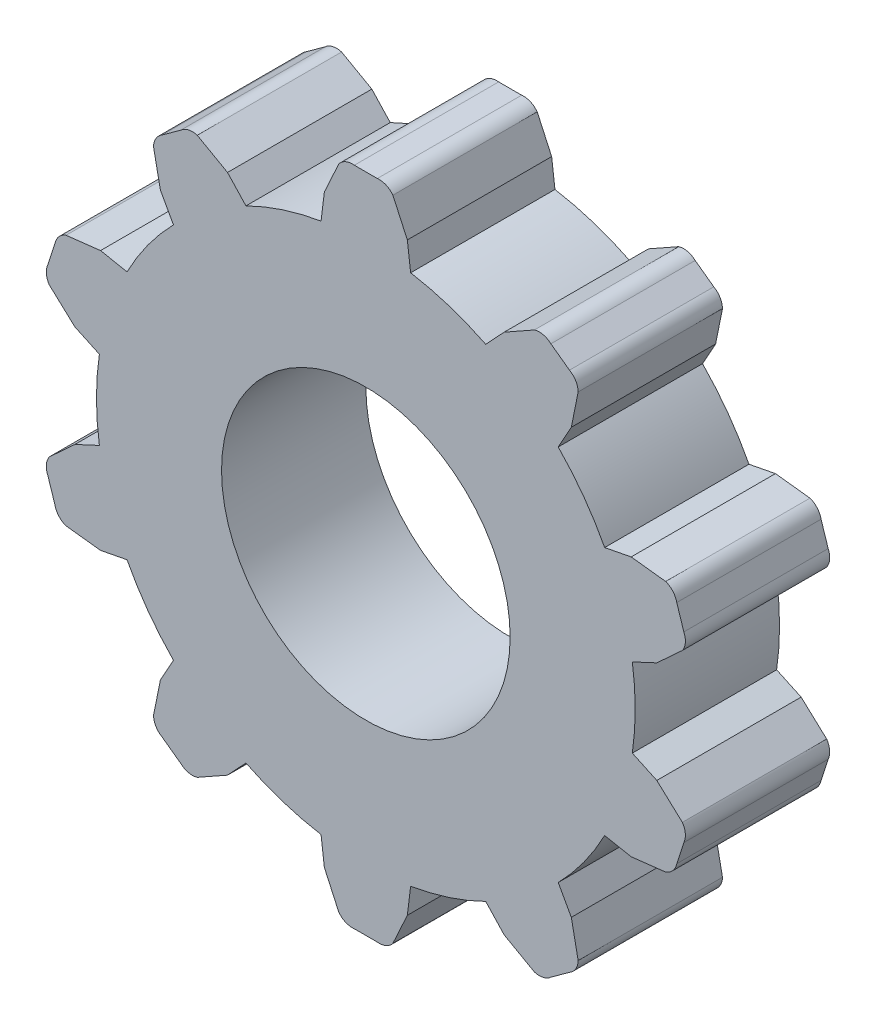
SolidWorks part; units mm, degrees
ref_plane "Płaszczyzna przednia" through (0, 0, 0) normal (0, 0, 1) x (1, 0, 0)
ref_plane "Płaszczyzna górna" through (0, 0, 0) normal (0, 1, 0) x (1, 0, 0)
ref_plane "Płaszczyzna prawa" through (0, 0, 0) normal (1, 0, 0) x (0, 0, -1)
sketch "Szkic1" plane through (0, 0, 0) normal (0, 0, 1) x (1, 0, 0)
  line L0 (0, 0) -> (-77.7801, 0) construction
  line L2 (-48.2003, 55.2206) -> (-47.5168, 60.795)
  line L3 (-47.5168, 60.795) -> (-44.5104, 67.3544)
  line L4 (-41.2805, 68.7348) -> (-36.4997, 68.7348)
  line L5 (-38.8901, 0) -> (-38.8901, 42.4347) construction
  line L6 (-29.5799, 55.2206) -> (-30.2633, 60.795)
  line L7 (-30.2633, 60.795) -> (-33.2697, 67.3544)
  line L8 (-10.1348, 54.2549) -> (-3.8471, 57.7944)
  line L9 (-13.9643, 50.1468) -> (-10.1348, 54.2549)
  line L10 (-0.4227, 57.0126) -> (3.4451, 54.2026)
  line L11 (3.8235, 44.1136) -> (5.2468, 51.1873)
  line L12 (1.0999, 39.202) -> (3.8235, 44.1136)
  line L13 (16.2636, 26.9912) -> (23.431, 26.1589)
  line L14 (10.7509, 25.9186) -> (16.2636, 26.9912)
  line L15 (25.7419, 23.5136) -> (27.2193, 18.9668)
  line L16 (21.5953, 10.5822) -> (26.9046, 15.4684)
  line L17 (16.5049, 8.2096) -> (21.5953, 10.5822)
  line L18 (21.5953, -10.5822) -> (26.9046, -15.4684)
  line L19 (16.5049, -8.2096) -> (21.5953, -10.5822)
  line L20 (27.2193, -18.9668) -> (25.7419, -23.5136)
  line L21 (16.2636, -26.9912) -> (23.431, -26.1589)
  line L22 (10.7509, -25.9186) -> (16.2636, -26.9912)
  line L23 (3.8235, -44.1136) -> (5.2468, -51.1873)
  line L24 (1.0999, -39.202) -> (3.8235, -44.1136)
  line L25 (3.4451, -54.2026) -> (-0.4227, -57.0126)
  line L26 (-10.1348, -54.2549) -> (-3.8471, -57.7944)
  line L27 (-13.9643, -50.1468) -> (-10.1348, -54.2549)
  line L28 (-30.2633, -60.795) -> (-33.2697, -67.3544)
  line L29 (-29.5799, -55.2206) -> (-30.2633, -60.795)
  line L30 (-36.4997, -68.7348) -> (-41.2805, -68.7348)
  line L31 (-47.5168, -60.795) -> (-44.5104, -67.3544)
  line L32 (-48.2003, -55.2206) -> (-47.5168, -60.795)
  line L33 (-67.6453, -54.2549) -> (-73.9331, -57.7944)
  line L34 (-63.8158, -50.1468) -> (-67.6453, -54.2549)
  line L35 (-77.3575, -57.0126) -> (-81.2252, -54.2026)
  line L36 (-81.6037, -44.1136) -> (-83.027, -51.1873)
  line L37 (-78.8801, -39.202) -> (-81.6037, -44.1136)
  line L38 (-94.0438, -26.9912) -> (-101.2112, -26.1589)
  line L39 (-88.531, -25.9186) -> (-94.0438, -26.9912)
  line L40 (-103.522, -23.5136) -> (-104.9994, -18.9668)
  line L41 (-99.3754, -10.5822) -> (-104.6847, -15.4684)
  line L42 (-94.285, -8.2096) -> (-99.3754, -10.5822)
  line L43 (-99.3754, 10.5822) -> (-104.6847, 15.4684)
  line L44 (-94.285, 8.2096) -> (-99.3754, 10.5822)
  line L45 (-104.9994, 18.9668) -> (-103.522, 23.5136)
  line L46 (-94.0438, 26.9912) -> (-101.2112, 26.1589)
  line L47 (-88.531, 25.9186) -> (-94.0438, 26.9912)
  line L48 (-81.6037, 44.1136) -> (-83.027, 51.1873)
  line L49 (-78.8801, 39.202) -> (-81.6037, 44.1136)
  line L50 (-81.2252, 54.2026) -> (-77.3575, 57.0126)
  line L51 (-67.6453, 54.2549) -> (-73.9331, 57.7944)
  line L52 (-63.8158, 50.1468) -> (-67.6453, 54.2549)
  circle A0 centre (-38.8901, 0) radius 30
  arc A1 (-78.8801, 39.202) -> (-88.531, 25.9186) centre (-38.8901, 0) ccw
  arc A2 (-44.5104, 67.3544) -> (-41.2805, 68.7348) centre (-41.6821, 65.2055) cw
  arc A3 (-33.2697, 67.3544) -> (-36.4997, 68.7348) centre (-36.098, 65.2055) ccw
  arc A4 (-3.8471, 57.7944) -> (-0.4227, 57.0126) centre (-2.8221, 54.3935) cw
  arc A5 (5.2468, 51.1873) -> (3.4451, 54.2026) centre (1.6956, 51.1112) ccw
  arc A6 (23.431, 26.1589) -> (25.7419, 23.5136) centre (22.2612, 22.805) cw
  arc A7 (26.9046, 15.4684) -> (27.2193, 18.9668) centre (23.9868, 17.4942) ccw
  arc A8 (26.9046, -15.4684) -> (27.2193, -18.9668) centre (23.9868, -17.4942) cw
  arc A9 (23.431, -26.1589) -> (25.7419, -23.5136) centre (22.2612, -22.805) ccw
  arc A10 (5.2468, -51.1873) -> (3.4451, -54.2026) centre (1.6956, -51.1112) cw
  arc A11 (-3.8471, -57.7944) -> (-0.4227, -57.0126) centre (-2.8221, -54.3935) ccw
  arc A12 (-33.2697, -67.3544) -> (-36.4997, -68.7348) centre (-36.098, -65.2055) cw
  arc A13 (-44.5104, -67.3544) -> (-41.2805, -68.7348) centre (-41.6821, -65.2055) ccw
  arc A14 (-73.9331, -57.7944) -> (-77.3575, -57.0126) centre (-74.9581, -54.3935) cw
  arc A15 (-83.027, -51.1873) -> (-81.2252, -54.2026) centre (-79.4757, -51.1112) ccw
  arc A16 (-101.2112, -26.1589) -> (-103.522, -23.5136) centre (-100.0414, -22.805) cw
  arc A17 (-104.6847, -15.4684) -> (-104.9994, -18.9668) centre (-101.7669, -17.4942) ccw
  arc A18 (-104.6847, 15.4684) -> (-104.9994, 18.9668) centre (-101.7669, 17.4942) cw
  arc A19 (-101.2112, 26.1589) -> (-103.522, 23.5136) centre (-100.0414, 22.805) ccw
  arc A20 (-83.027, 51.1873) -> (-81.2252, 54.2026) centre (-79.4757, 51.1112) cw
  arc A21 (-73.9331, 57.7944) -> (-77.3575, 57.0126) centre (-74.9581, 54.3935) ccw
  arc A22 (-94.285, 8.2096) -> (-94.285, -8.2096) centre (-38.8901, 0) ccw
  arc A23 (-88.531, -25.9186) -> (-78.8801, -39.202) centre (-38.8901, 0) ccw
  arc A24 (-63.8158, -50.1468) -> (-48.2003, -55.2206) centre (-38.8901, 0) ccw
  arc A25 (-29.5799, -55.2206) -> (-13.9643, -50.1468) centre (-38.8901, 0) ccw
  arc A26 (1.0999, -39.202) -> (10.7509, -25.9186) centre (-38.8901, 0) ccw
  arc A27 (16.5049, -8.2096) -> (16.5049, 8.2096) centre (-38.8901, 0) ccw
  arc A28 (10.7509, 25.9186) -> (1.0999, 39.202) centre (-38.8901, 0) ccw
  arc A29 (-13.9643, 50.1468) -> (-29.5799, 55.2206) centre (-38.8901, 0) ccw
  arc A30 (-48.2003, 55.2206) -> (-63.8158, 50.1468) centre (-38.8901, 0) ccw
  point P9 (-38.8901, 53.2791)
  point P19 (-38.8901, 68.7348)
  dimension "D1" = 10
extrude "Dodanie-wyciągnięcie1" add sketch "Szkic1" along normal blind 30
